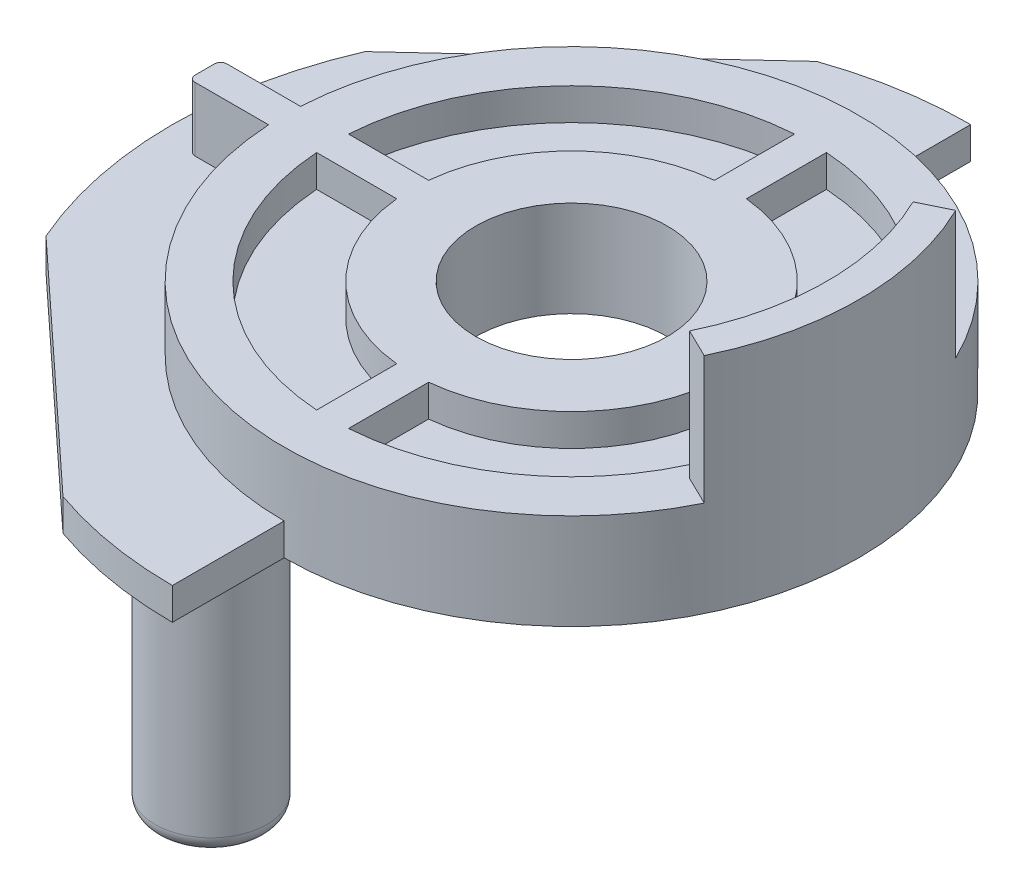
SolidWorks part; units mm, degrees
material "ABS PC"
ref_plane "Piano frontale" through (0, 0, 0) normal (0, 0, 1) x (1, 0, 0)
ref_plane "Piano superiore" through (0, 0, 0) normal (0, 1, 0) x (1, 0, 0)
ref_plane "Piano destro" through (0, 0, 0) normal (1, 0, 0) x (0, 0, -1)
sketch "Schizzo1" plane through (0, 0, 0) normal (0, 1, 0) x (1, 0, 0)
  circle A0 centre (0, 0) radius 3
  circle A1 centre (0, 0) radius 9
  dimension "D1" = 6
  dimension "D2" = 18
extrude "Estrusione-Estrusione1" add sketch "Schizzo1" along normal blind 7
sketch "Schizzo3" plane through (0, 7, 0) normal (0, 1, 0) x (1, 0, 0)
  line L0 (0, 0) -> (8.093, 3.9375) construction
  line L1 (0, 0) -> (8.093, -3.9375) construction
  line L2 (7.1937, 3.5) -> (7.1937, -3.5) construction
  line L3 (7.1937, 3.5) -> (8.093, 3.9375)
  line L4 (7.1937, -3.5) -> (8.093, -3.9375)
  circle A0 centre (0, 0) radius 9 construction
  arc A1 (8.093, 3.9375) -> (8.093, -3.9375) centre (0, 0) ccw
  arc A2 (7.1937, -3.5) -> (7.1937, 3.5) centre (0, 0) ccw
  circle A3 centre (0, 0) radius 9 construction
  circle A4 centre (0, 0) radius 8 construction
  dimension "D2" = 7
  dimension "D1" = 1
extrude "Taglio-Estrusione1" cut sketch "Schizzo3" against normal offset from surface (4 mm away) 3 up to face at (0, 0, 9)
sketch "Schizzo4" plane through (0, 3, 0) normal (0, 1, 0) x (1, 0, 0)
  line L0 (0, 0) -> (0, 7.4833) construction
  line L1 (0, 0) -> (-7.4833, 0) construction
  line L2 (-0.5, 0) -> (-0.5, 0.5)
  line L3 (0, 0.5) -> (-0.5, 0.5)
  line L4 (-4.9749, 0.5) -> (-7.4833, 0.5)
  line L5 (0, 0.5) -> (-7.4833, 0.5) construction
  line L6 (-0.5, 4.9749) -> (-0.5, 7.4833)
  line L7 (-0.5, 0) -> (-0.5, 7.4833) construction
  circle A2 centre (0, 0) radius 5
  arc A3 (-0.5, 4.9749) -> (-4.9749, 0.5) centre (0, 0) ccw
  arc A4 (-0.5, 7.4833) -> (-7.4833, 0.5) centre (0, 0) ccw
  dimension "D2" = 15
  dimension "D1" = 2
  dimension "D3" = 0.5
  dimension "D4" = 0.5
extrude "Taglio-Estrusione2" cut sketch "Schizzo4" against normal blind 1 contours L6 A4 L4 A3
pattern_circular "RipetizioneCircolare1" count 4 over 360 about axis through (0, 0, 0) along (0, 1, 0) of "Taglio-Estrusione2"
sketch "Schizzo5" plane through (0, 0, 0) normal (0, 1, 0) x (1, 0, 0)
  line L0 (0, 12.5) -> (0, -12.5) construction
  line L1 (0, 9) -> (0, 12.5)
  line L2 (0, -9) -> (0, -12.5)
  line L3 (-4.1243, 11.8) -> (-11.4564, 5)
  line L4 (-11.4564, -5) -> (-4.1243, -11.8)
  arc A0 (8.093, 3.9375) -> (8.093, -3.9375) centre (0, 0) ccw construction
  arc A1 (0, 9) -> (0, -9) centre (0, 0) ccw
  arc A2 (0, 12.5) -> (-4.1243, 11.8) centre (0, 0) ccw
  arc A3 (-11.4564, 5) -> (-11.4564, -5) centre (0, 0) ccw
  arc A4 (-4.1243, -11.8) -> (0, -12.5) centre (0, 0) ccw
  dimension "D1" = 25
  dimension "D2" = 10
  dimension "D3" = 10
extrude "Estrusione-Estrusione2" add sketch "Schizzo5" along normal blind 1
sketch "Schizzo6" plane through (0, 1, 0) normal (0, 1, 0) x (1, 0, 0)
  line L0 (-8.9861, 0.5) -> (-11.2861, 0.5)
  line L1 (-8.9861, -0.5) -> (-11.2861, -0.5)
  line L2 (-11.4861, -0.3) -> (-11.4861, 0.3)
  line L3 (-4.9749, 0.5) -> (-7.4833, 0.5) construction
  line L4 (-4.9749, -0.5) -> (-7.4833, -0.5) construction
  arc A0 (8.093, 3.9375) -> (8.093, -3.9375) centre (0, 0) ccw construction
  arc A1 (0, 9) -> (0, -9) centre (0, 0) ccw construction
  arc A2 (-8.9861, 0.5) -> (-8.9861, -0.5) centre (0, 0) ccw
  arc A3 (-11.4861, 0.3) -> (-11.2861, 0.5) centre (-11.2861, 0.3) cw
  arc A4 (-11.4861, -0.3) -> (-11.2861, -0.5) centre (-11.2861, -0.3) ccw
  point P16 (-11.4861, 0.5)
  dimension "D2" = 0.2
  dimension "D3" = 0.2
  dimension "D1" = 2.5
extrude "Estrusione-Estrusione3" add sketch "Schizzo6" along normal up to surface (2 mm away) up to face at (3.892, 3, -3.892)
sketch "Schizzo7" plane through (0, 0, 0) normal (0, -1, 0) x (1, 0, 0)
  line L0 (0, 0) -> (-12.5, 0) construction
  line L1 (-9.2871, 2) -> (-9.2871, 0) construction
  arc A0 (-11.4564, 5) -> (-11.4564, -5) centre (0, 0) ccw construction
  circle A1 centre (-9.2871, 2) radius 1.75
  dimension "D1" = 3.5
  dimension "D2" = 9.5
  dimension "D3" = 2
extrude "Estrusione-Estrusione4" add sketch "Schizzo7" along normal blind 15
fillet "Raccordo1" radius 0.5 1 edges at (-9.2871, -15, 0.25)
